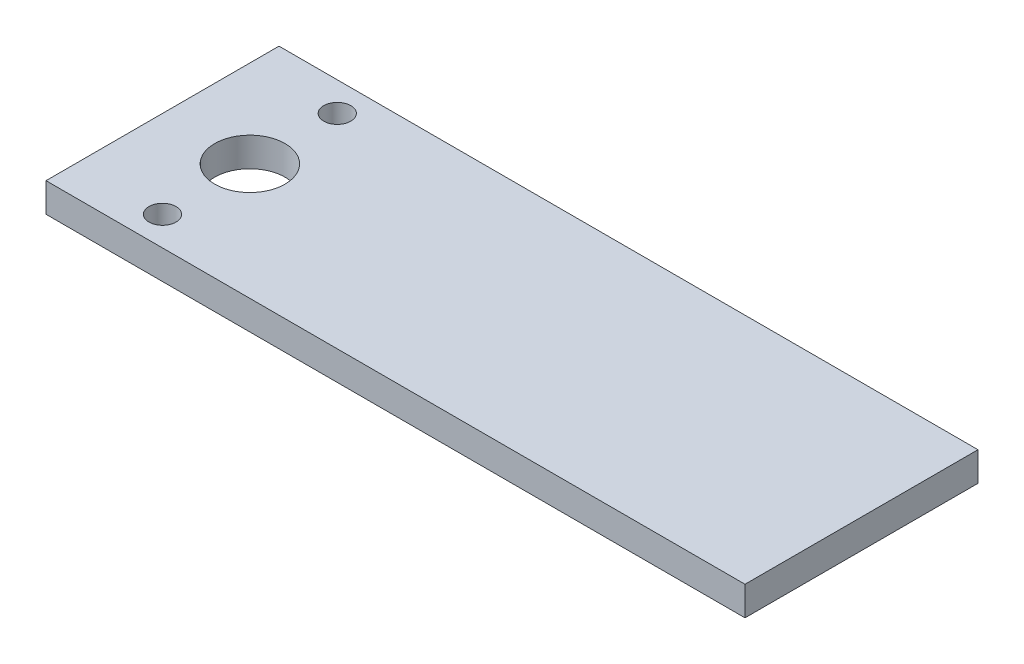
SolidWorks part; units mm, degrees
ref_plane "Front" through (0, 0, 0) normal (0, 0, 1) x (1, 0, 0)
ref_plane "Top" through (0, 0, 0) normal (0, 1, 0) x (1, 0, 0)
ref_plane "Right" through (0, 0, 0) normal (1, 0, 0) x (0, 0, -1)
sketch "Sketch1" plane through (0, 0, 0) normal (0, 1, 0) x (1, 0, 0)
  line L0 (9.525, 25.4) -> (9.525, 0) construction
  line L1 (0, 0) -> (76.2, 0)
  line L2 (0, 0) -> (0, 25.4)
  line L3 (0, 25.4) -> (76.2, 25.4)
  line L4 (76.2, 0) -> (76.2, 25.4)
  line L6 (0, 12.7) -> (9.525, 12.7) construction
  circle A0 centre (9.525, 22.225) radius 1.4732
  circle A1 centre (9.525, 3.175) radius 1.4732
  circle A2 centre (9.525, 12.7) radius 3.8354
  dimension "D2" = 2.9464
  dimension "D4" = 19.05
  dimension "D5" = 7.6708
  dimension "D1" = 76.2
  dimension "D3" = 25.4
  dimension "D6" = 9.525
extrude "Boss-Extrude1" add sketch "Sketch1" along normal blind 3.175
